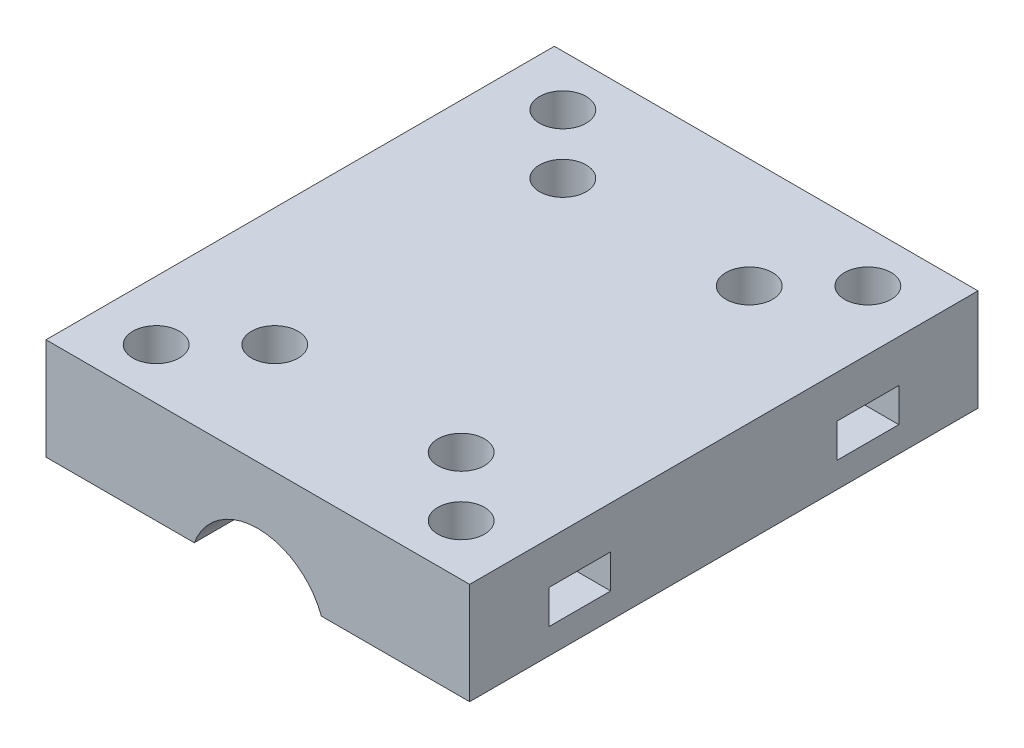
SolidWorks part; units mm, degrees
material "ABS PC"
ref_plane "Front Plane" through (0, 0, 0) normal (0, 0, 1) x (1, 0, 0)
ref_plane "Top Plane" through (0, 0, 0) normal (0, 1, 0) x (1, 0, 0)
ref_plane "Right Plane" through (0, 0, 0) normal (1, 0, 0) x (0, 0, -1)
sketch "Sketch1" plane through (0, 0, 0) normal (0, 1, 0) x (1, 0, 0)
  line L0 (0, 0) -> (50, 0)
  line L1 (0, 0) -> (0, 60)
  line L2 (50, 0) -> (50, 60)
  line L3 (0, 60) -> (50, 60)
  dimension "D1" = 50
  dimension "D2" = 60
extrude "Boss-Extrude1" add sketch "Sketch1" along normal blind 12
sketch "Sketch2" plane through (0, 0, 0) normal (0, 0, 1) x (1, 0, 0)
  line L0 (17.5, 0) -> (32.5, 0)
  line L1 (0, 0) -> (50, 0) construction
  arc A0 (17.5, 0) -> (32.5, 0) centre (25, -2.7839) cw
  dimension "D3" = 8
  dimension "D1" = 15
  dimension "D2" = 17.5
extrude "Cut-Extrude1" cut sketch "Sketch2" against normal through all
hole_wizard "Ø5.5 (5.5) Diameter Hole1" positions "Sketch4" profile "Sketch3" hole size "Ø5.5" standard "Ansi Metric"
sketch "Sketch4" plane through (0, 0, 0) normal (0, -1, 0) x (1, 0, 0)
  line L0 (0, -60) -> (0, 0) construction
  line L1 (50, 0) -> (50, -60) construction
  line L2 (0, 0) -> (17.5, 0) construction
  line L3 (17.5, -60) -> (0, -60) construction
  point P0 (14, -13)
  point P1 (36, -13)
  point P3 (14, -47)
  point P5 (36, -47)
  dimension "D1" = 14
  dimension "D2" = 14
  dimension "D3" = 13
  dimension "D4" = 13
sketch "Sketch3" plane through (14, 0, -13) normal (1, 0, 0) x (0, 0, -1)
  line L0 (0, 0) -> (0, 31.6524)
  line L1 (0, 31.6524) -> (2.75, 30)
  line L2 (2.75, 30) -> (2.75, 0)
  line L5 (2.75, 0) -> (0, 0)
  line L10 (0, 31.6524) -> (-2.75, 30) construction
  line L11 (0, -6.35) -> (0, 107.95) construction
  dimension "Hole Dia." = 5.5
  dimension "Hole Depth" = 30
  dimension "Drill Angle" = 118
sketch "Sketch5" plane through (0, 0, 0) normal (-1, 0, 0) x (0, 0, 1)
  line L0 (-50.65, 7) -> (-50.65, 3)
  line L1 (-50.65, 7) -> (-43.35, 7)
  line L2 (-50.65, 3) -> (-43.35, 3)
  line L3 (-43.35, 7) -> (-43.35, 3)
  line L4 (-16.65, 7) -> (-16.65, 3)
  line L5 (-16.65, 7) -> (-9.35, 7)
  line L6 (-16.65, 3) -> (-9.35, 3)
  line L7 (-9.35, 7) -> (-9.35, 3)
  line L8 (-60, 12) -> (-60, 0) construction
  line L9 (0, 12) -> (0, 0) construction
  line L10 (-60, 0) -> (0, 0) construction
  dimension "D1" = 7.3
  dimension "D2" = 4
  dimension "D3" = 9.35
  dimension "D4" = 9.35
  dimension "D5" = 3
extrude "Cut-Extrude2" cut sketch "Sketch5" against normal blind 17.3
sketch "Sketch6" plane through (50, 0, 0) normal (1, 0, 0) x (0, 0, -1)
  line L0 (9.35, 7) -> (9.35, 3)
  line L1 (9.35, 7) -> (16.65, 7)
  line L2 (9.35, 3) -> (16.65, 3)
  line L3 (16.65, 7) -> (16.65, 3)
  line L4 (43.35, 7) -> (43.35, 3)
  line L5 (43.35, 7) -> (50.65, 7)
  line L6 (43.35, 3) -> (50.65, 3)
  line L7 (50.65, 7) -> (50.65, 3)
  line L11 (60, 12) -> (60, 0) construction
  line L12 (0, 12) -> (0, 0) construction
  line L13 (0, 0) -> (60, 0) construction
  dimension "D1" = 7.3
  dimension "D2" = 4
  dimension "D3" = 9.35
  dimension "D4" = 9.35
  dimension "D5" = 3
extrude "Cut-Extrude3" cut sketch "Sketch6" against normal blind 17.3
hole_wizard "Ø5.5 (5.5) Diameter Hole2" positions "Sketch8" profile "Sketch7" hole size "Ø5.5" standard "Ansi Metric" end condition through all
sketch "Sketch8" plane through (0, 12, 0) normal (0, 1, 0) x (-1, 0, 0)
  line L0 (-50, 0) -> (-50, -60) construction
  line L1 (0, 0) -> (-50, 0) construction
  line L2 (0, -60) -> (0, 0) construction
  line L3 (-50, -60) -> (0, -60) construction
  point P0 (-43, -6)
  point P1 (-7, -6)
  point P3 (-7, -54)
  point P5 (-43, -54)
  dimension "D1" = 7
  dimension "D2" = 6
  dimension "D3" = 7
  dimension "D4" = 6
sketch "Sketch7" plane through (43, 12, -6) normal (1, 0, 0) x (0, 0, 1)
  line L0 (0, 0) -> (0, 12)
  line L1 (0, 12) -> (2.75, 12)
  line L2 (2.75, 12) -> (2.75, 0)
  line L5 (2.75, 0) -> (0, 0)
  line L11 (0, -6.35) -> (0, 107.95) construction
  dimension "Thru Hole Dia." = 5.5
  dimension "Thru Hole Depth" = 12
